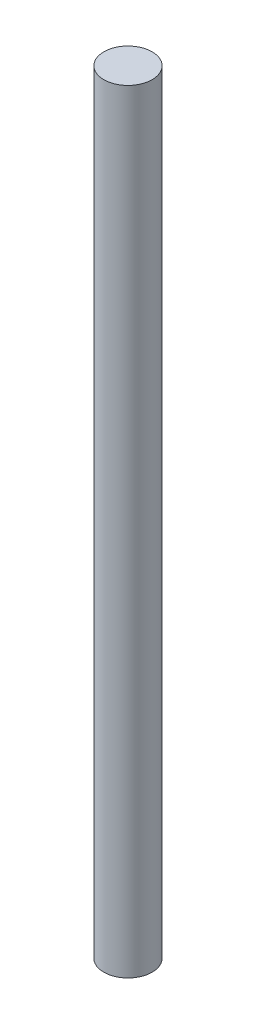
SolidWorks part; units mm, degrees
ref_plane "Front Plane" through (0, 0, 0) normal (0, 0, 1) x (1, 0, 0)
ref_plane "Top Plane" through (0, 0, 0) normal (0, 1, 0) x (1, 0, 0)
ref_plane "Right Plane" through (0, 0, 0) normal (1, 0, 0) x (0, 0, -1)
sketch "Sketch2" plane through (0, 0, 0) normal (0, 1, 0) x (1, 0, 0)
  circle A0 centre (0, 0) radius 3.175
  dimension "D1" = 6.35
extrude "Boss-Extrude1" add sketch "Sketch2" along normal mid plane 101.6
equation "\"length\"= 4in"
equation "\"D1@Boss-Extrude1\"=\"length\""
